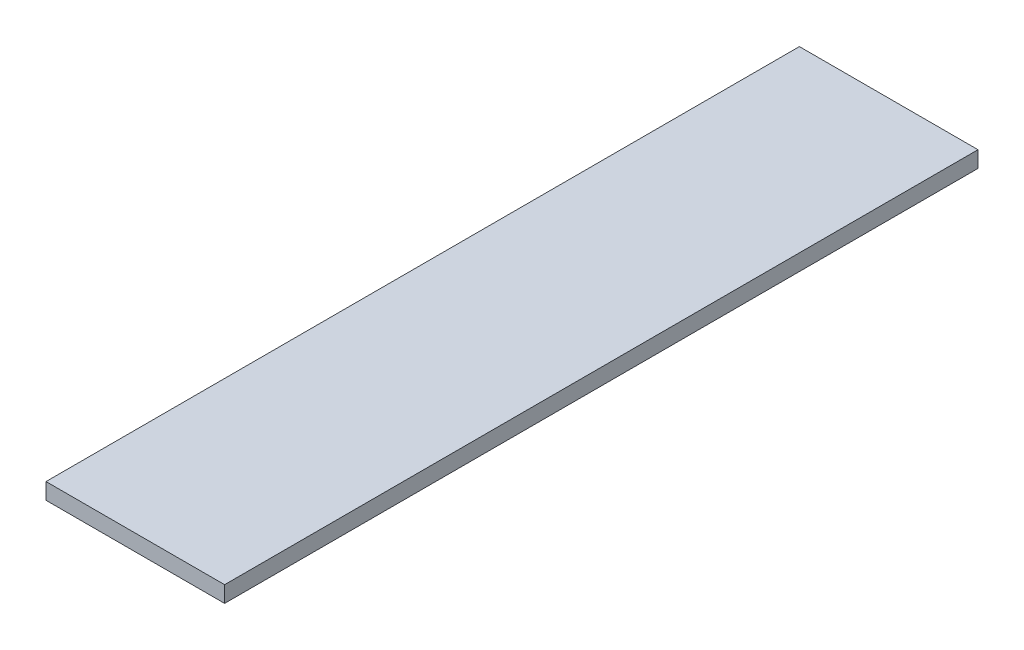
SolidWorks part; units mm, degrees
ref_plane "Front Plane" through (0, 0, 0) normal (0, 0, 1) x (1, 0, 0)
ref_plane "Top Plane" through (0, 0, 0) normal (0, 1, 0) x (1, 0, 0)
ref_plane "Right Plane" through (0, 0, 0) normal (1, 0, 0) x (0, 0, -1)
sketch "Sketch1" plane through (0, 0, 0) normal (0, 0, 1) x (1, 0, 0)
  line L1 (0, 0) -> (69.85, 0)
  line L2 (0, 0) -> (0, 6.35)
  line L3 (0, 6.35) -> (69.85, 6.35)
  line L4 (69.85, 0) -> (69.85, 6.35)
  dimension "D1" = 69.85
  dimension "D2" = 6.35
extrude "Boss-Extrude1" add sketch "Sketch1" along normal blind 294.64
